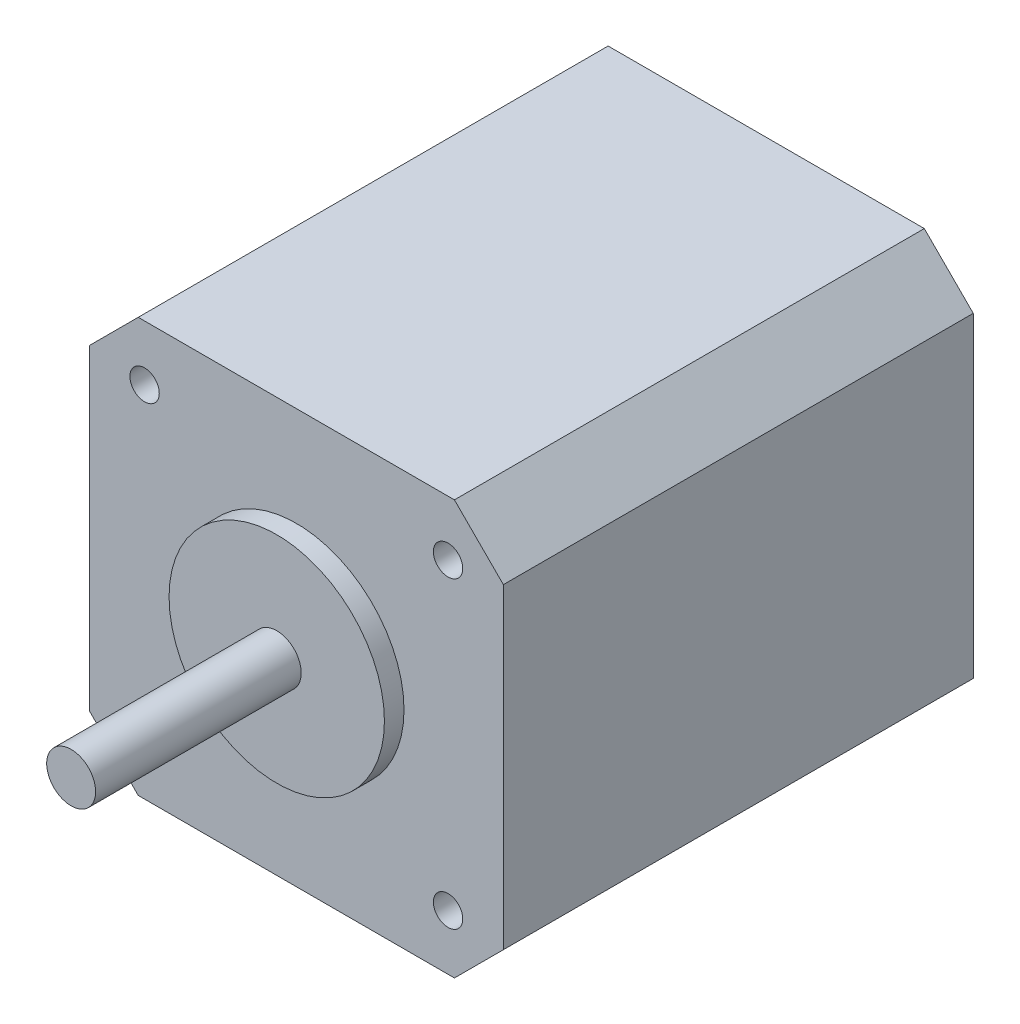
SolidWorks part; units mm, degrees
ref_plane "Front Plane" through (0, 0, 0) normal (0, 0, 1) x (1, 0, 0)
ref_plane "Top Plane" through (0, 0, 0) normal (0, 1, 0) x (1, 0, 0)
ref_plane "Right Plane" through (0, 0, 0) normal (1, 0, 0) x (0, 0, -1)
sketch "Sketch1" plane through (0, 0, 0) normal (0, 0, 1) x (1, 0, 0)
  line L1 (-21.15, 21.15) -> (21.15, 21.15)
  line L2 (-21.15, 21.15) -> (-21.15, -21.15)
  line L3 (-21.15, -21.15) -> (21.15, -21.15)
  line L4 (21.15, 21.15) -> (21.15, -21.15)
  line L5 (-21.15, 21.15) -> (21.15, -21.15) construction
  line L6 (-21.15, -21.15) -> (21.15, 21.15) construction
  point P0 (0, 0)
  dimension "D1" = 42.3
extrude "Boss-Extrude1" add sketch "Sketch1" against normal blind 48
chamfer "Chamfer1" distance 5 angle 45 4 edges at (-21.15, -21.15, -24) (21.15, -21.15, -24) (21.15, 21.15, -24) (-21.15, 21.15, -24)
sketch "Sketch3" plane through (0, 0, 0) normal (0, 0, 1) x (1, 0, 0)
  line L0 (0, 0) -> (0, -15.5) construction
  line L1 (0, -15.5) -> (15.5, -15.5) construction
  circle A0 centre (15.5, -15.5) radius 1.5
  circle A1 centre (-15.5, -15.5) radius 1.5
  circle A2 centre (-15.5, 15.5) radius 1.5
  circle A3 centre (15.5, 15.5) radius 1.5
  dimension "D3" = 3
  dimension "D1" = 15.5
  dimension "D2" = 15.5
  dimension "D4" = 4
extrude "Cut-Extrude1" cut sketch "Sketch3" against normal blind 5
sketch "Sketch4" plane through (0, 0, 0) normal (0, 0, 1) x (1, 0, 0)
  circle A0 centre (0, 0) radius 11
  dimension "D1" = 22
extrude "Boss-Extrude2" add sketch "Sketch4" along normal blind 2
sketch "Sketch5" plane through (0, 0, 0) normal (0, 0, 1) x (1, 0, 0)
  circle A0 centre (0, 0) radius 2.5
  dimension "D1" = 5
extrude "Boss-Extrude3" add sketch "Sketch5" along normal blind 23
sketch "Sketch6" plane through (0, 0, -48) normal (0, 0, -1) x (-1, 0, 0)
  line L0 (16.15, -21.15) -> (-16.15, -21.15) construction
  line L1 (-8, -28.15) -> (8, -28.15)
  line L2 (-8, -28.15) -> (-8, -21.15)
  line L3 (-8, -21.15) -> (8, -21.15)
  line L4 (8, -28.15) -> (8, -21.15)
  line L5 (-8, -28.15) -> (8, -21.15) construction
  line L6 (-8, -21.15) -> (8, -28.15) construction
  point P0 (0, -24.65)
  point P5 (0, 0)
  dimension "D1" = 7
  dimension "D2" = 16
extrude "Boss-Extrude4" add sketch "Sketch6" against normal blind 9.6
